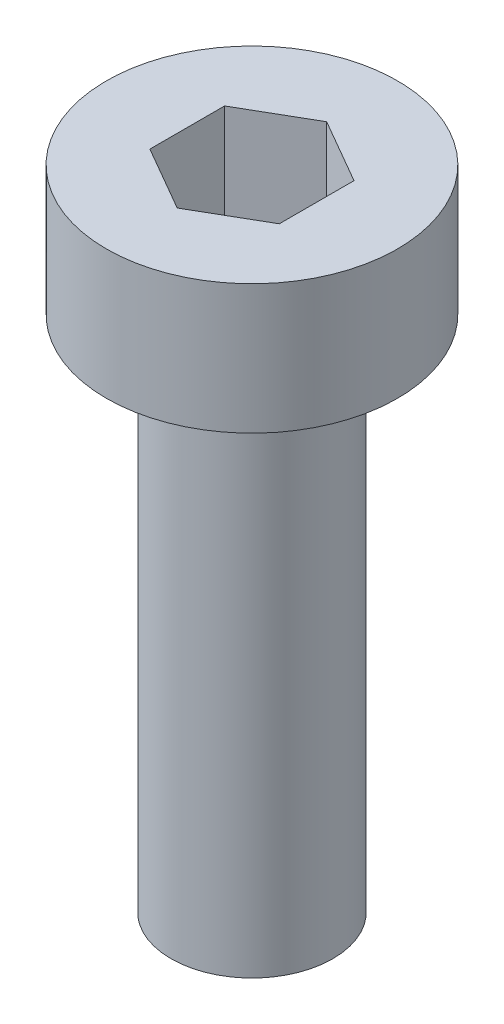
SolidWorks part; units mm, degrees
material "灰铸铁"
ref_plane "前视基准面" through (0, 0, 0) normal (0, 0, 1) x (1, 0, 0)
ref_plane "上视基准面" through (0, 0, 0) normal (0, 1, 0) x (1, 0, 0)
ref_plane "右视基准面" through (0, 0, 0) normal (1, 0, 0) x (0, 0, -1)
other "Configuration Table"
sketch "草图1" plane through (0, 0, 0) normal (0, 1, 0) x (1, 0, 0)
  line L1 (0, 1.1547) -> (-1, 0.5774)
  line L2 (-1, 0.5774) -> (-1, -0.5774)
  line L3 (-1, -0.5774) -> (0, -1.1547)
  line L4 (0, -1.1547) -> (1, -0.5774)
  line L5 (1, -0.5774) -> (1, 0.5774)
  line L6 (1, 0.5774) -> (0, 1.1547)
  circle A0 centre (0, 0) radius 2.25
  circle A1 centre (0, 0) radius 1 construction
  dimension "D1" = 4.5
  dimension "D2" = 2
extrude "凸台-拉伸1" add sketch "草图1" along normal blind 2
sketch "草图2" plane through (0, 0, 0) normal (0, -1, 0) x (1, 0, 0)
  circle A0 centre (0, 0) radius 1.25
  dimension "D1" = 2.5
extrude "凸台-拉伸2" add sketch "草图2" along normal blind 8
